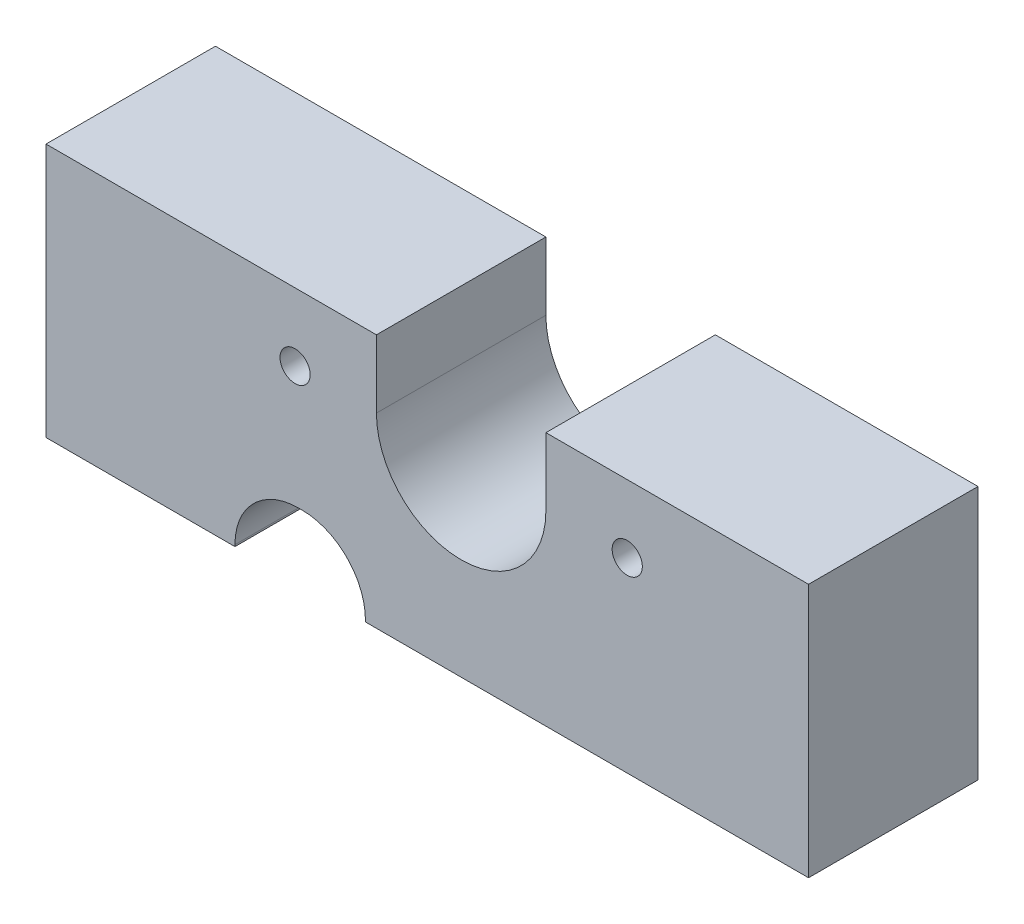
SolidWorks part; units mm, degrees
material "ABS PC"
ref_plane "Front Plane" through (0, 0, 0) normal (0, 0, 1) x (1, 0, 0)
ref_plane "Top Plane" through (0, 0, 0) normal (0, 1, 0) x (1, 0, 0)
ref_plane "Right Plane" through (0, 0, 0) normal (1, 0, 0) x (0, 0, -1)
sketch "Sketch1" plane through (0, 0, 0) normal (1, 0, 0) x (0, 0, -1)
  line L1 (0, 0) -> (12.7, 0)
  line L2 (0, 0) -> (0, 19.05)
  line L3 (0, 19.05) -> (12.7, 19.05)
  line L4 (12.7, 0) -> (12.7, 19.05)
  dimension "D1" = 12.7
  dimension "D2" = 19.05
extrude "Boss-Extrude1" add sketch "Sketch1" against normal blind 57.15
hole_wizard "#6-32 Tapped Hole1" positions "Sketch4" profile "Sketch3" tap size "#6-32" standard "ANSI Inch"
sketch "Sketch4" plane through (23.2872, 0, 3.1883) normal (0, 1, 0) x (1, 0, 0)
  line L0 (-23.2872, 15.8883) -> (-23.2872, 3.1883) construction
  line L3 (-23.2872, 9.5383) -> (-80.4372, 9.5383) construction
  line L4 (-80.4372, 15.8883) -> (-80.4372, 3.1883) construction
  point P0 (-29.6372, 9.5383)
  point P2 (-74.0872, 9.5383)
  dimension "D1" = 6.35
  dimension "D2" = 44.45
sketch "Sketch3" plane through (-6.35, 0, -6.35) normal (1, 0, 0) x (0, 0, -1)
  line L0 (0, 0) -> (0, 13.5127)
  line L1 (0, 13.5127) -> (1.3525, 12.7)
  line L2 (1.3525, 12.7) -> (1.3525, 10.795)
  line L3 (1.3525, 10.795) -> (1.7526, 10.795)
  line L4 (1.7526, 10.795) -> (1.7526, 0)
  line L5 (1.7526, 0) -> (0, 0)
  line L10 (0, 13.5127) -> (-1.3526, 12.7) construction
  line L11 (0, -6.35) -> (0, 107.95) construction
  dimension "Tap Drill Dia." = 2.7051
  dimension "Tap Drill Depth" = 12.7
  dimension "Thread Major Dia." = 3.5052
  dimension "Thread Depth" = 10.795
  dimension "Drill Angle" = 118
sketch "Sketch5" plane through (0, 0, -12.7) normal (0, 0, -1) x (-1, 0, 0)
  line L0 (57.15, 19.05) -> (0, 19.05) construction
  line L1 (0, 0) -> (0, 19.05) construction
  line L6 (26.035, 5.08) -> (26.035, 28.2578) construction
  line L7 (26.035, 19.05) -> (26.035, 13.97) construction
  line L8 (32.385, 19.05) -> (32.385, 13.97)
  line L9 (19.685, 19.05) -> (19.685, 13.97)
  arc A2 (32.385, 19.05) -> (19.685, 19.05) centre (26.035, 19.05) ccw
  arc A3 (19.685, 13.97) -> (32.385, 13.97) centre (26.035, 13.97) ccw
  point P1 (26.035, 19.05)
  point P18 (26.035, 16.51)
  dimension "D3" = 5.08
  dimension "D1" = 26.035
  dimension "D2" = 12.7
extrude "Cut-Extrude2" cut sketch "Sketch5" against normal through all
hole_wizard "#4-40 Tapped Hole1" positions "Sketch11" profile "Sketch10" tap size "#4-40" standard "ANSI Inch" end condition through all
sketch "Sketch11" plane through (0, 0, -12.7) normal (0, 0, -1) x (-1, 0, 0)
  line L0 (26.035, 13.97) -> (26.035, 37.9737) construction
  arc A0 (19.685, 13.97) -> (32.385, 13.97) centre (26.035, 13.97) ccw construction
  point P0 (13.589, 13.97)
  point P2 (38.481, 13.97)
  dimension "D1" = 24.892
sketch "Sketch10" plane through (-13.589, 13.97, -12.7) normal (1, 0, 0) x (0, 1, 0)
  line L0 (0, 0) -> (0, 12.7)
  line L1 (0, 12.7) -> (1.1303, 12.7)
  line L2 (1.1303, 12.7) -> (1.1303, 0)
  line L5 (1.1303, 0) -> (0, 0)
  line L11 (0, -6.35) -> (0, 107.95) construction
  dimension "Thru Tap Drill Dia." = 2.2606
  dimension "Thru Tap Drill Depth" = 12.7
cosmetic thread "Hole Thread2" parameters "D2"=2.8448
cosmetic thread "Hole Thread3" parameters "D2"=2.8448
sketch "Sketch6" plane through (0, 0, -12.7) normal (0, 0, -1) x (-1, 0, 0)
  line L0 (57.15, 0) -> (0, 0) construction
  line L3 (33.2105, 0) -> (42.9895, 0)
  line L4 (33.2105, 0) -> (33.2105, 0.127)
  line L5 (37.973, 4.8895) -> (38.227, 4.8895)
  line L6 (42.9895, 0) -> (42.9895, 0.127)
  arc A0 (38.227, 4.8895) -> (42.9895, 0.127) centre (38.227, 0.127) cw
  arc A1 (37.973, 4.8895) -> (33.2105, 0.127) centre (37.973, 0.127) ccw
  point P0 (38.1, 0)
  point P5 (42.9895, 4.8895)
  point P13 (33.2105, 4.8895)
  dimension "D2" = 4.7625
  dimension "D1" = 38.1
  dimension "D3" = 4.8895
  dimension "D4" = 9.779
extrude "Cut-Extrude3" cut sketch "Sketch6" against normal through all
